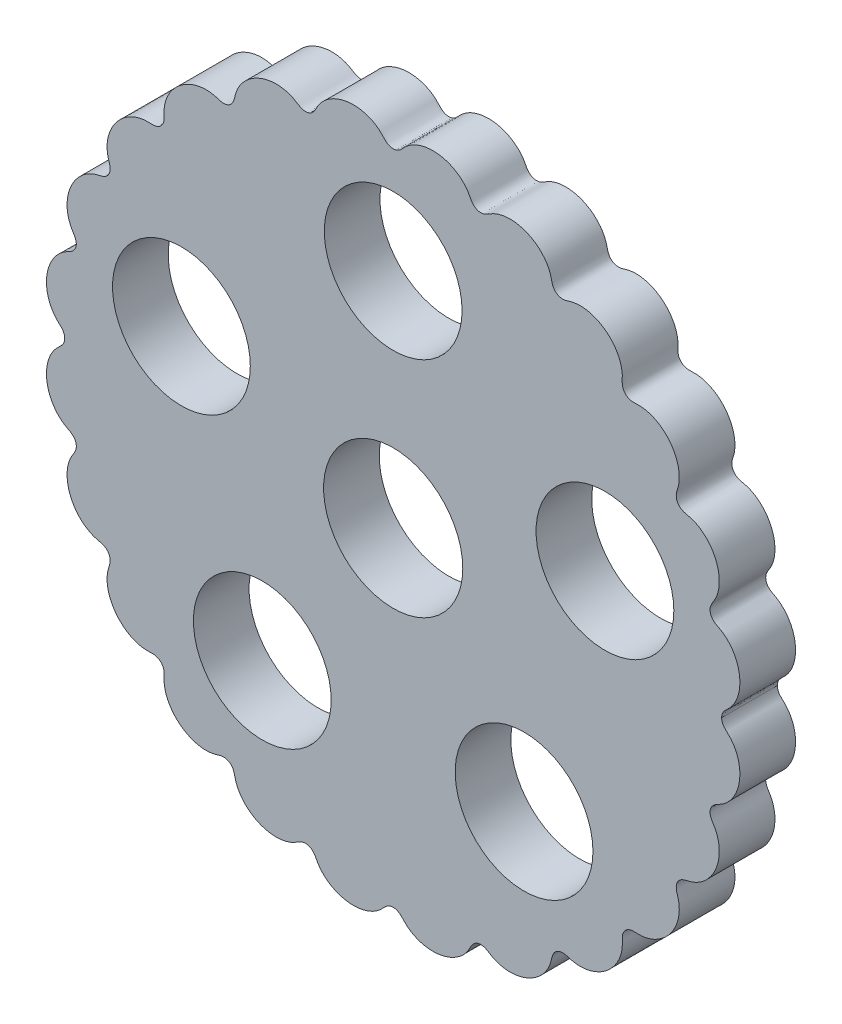
SolidWorks part; units mm, degrees
ref_plane "Plan de face" through (0, 0, 0) normal (0, 0, 1) x (1, 0, 0)
ref_plane "Plan de dessus" through (0, 0, 0) normal (0, 1, 0) x (1, 0, 0)
ref_plane "Plan de droite" through (0, 0, 0) normal (1, 0, 0) x (0, 0, -1)
sketch "Esquisse1" plane through (0, 0, 0) normal (0, 0, 1) x (1, 0, 0)
  line L0 (-1000, 0) -> (49000, 0) construction
  spline S0 degree 4 poles (22.9955, 6.6042) (22.9643, 6.5397) (22.914, 6.4032) (22.9023, 6.1862) (23.0214, 5.9244) (23.2219, 5.7605) (23.4288, 5.659) (23.6594, 5.5306) (23.9059, 5.3649) (24.1666, 5.1353) (24.4254, 4.835) (24.6422, 4.5029) (24.8162, 4.1468) (24.946, 3.7722) (25.0308, 3.385) (25.0698, 2.9906) (25.0624, 2.5943) (25.0079, 2.2017) (24.9068, 1.8224) (24.7781, 1.5066) (24.64, 1.2523) (24.5081, 1.0548) (24.3917, 0.9046) (24.2647, 0.7631) (24.1289, 0.6302) (24.012, 0.5251) (23.9248, 0.4355) (23.8688, 0.3622) (23.8363, 0.3122) (23.8082, 0.2597) (23.7852, 0.2044) (23.7697, 0.1547) (23.76, 0.1121) (23.7533, 0.0661) (23.7501, 0.0228) (23.7495, -0.004) (23.7513, -0.04) (23.7542, -0.0715) (23.7595, -0.1093) (23.7688, -0.1512) (23.7835, -0.1997) (23.8056, -0.2538) (23.8324, -0.3054) (23.8635, -0.3546) (23.9194, -0.4297) (24.009, -0.5227) (24.1313, -0.6322) (24.2737, -0.7721) (24.4392, -0.959) (24.6145, -1.2025) (24.7855, -1.5135) (24.9316, -1.8961) (25.0271, -2.299) (25.0708, -2.7153) (25.0622, -3.1311) (25.0033, -3.5401) (24.8958, -3.9363) (24.7419, -4.314) (24.5445, -4.6645) (24.307, -4.9822) (24.0331, -5.2614) (23.7654, -5.4667) (23.5164, -5.6129) (23.2956, -5.7243) (23.1195, -5.8363) (22.9763, -6.0087) (22.9044, -6.234) (22.925, -6.462) (23.0164, -6.6581) (23.1266, -6.8267) (23.2244, -6.9889) (23.3341, -7.1984) (23.4412, -7.4619) (23.5336, -7.7957) (23.5876, -8.2004) (23.5865, -8.623) (23.5267, -9.0558) (23.3808, -9.5868) (23.1436, -10.0885) (22.8209, -10.5434) (22.4327, -10.9196) (22.1006, -11.1627) (21.7948, -11.3267) (21.5321, -11.4304) (21.3065, -11.4954) (21.1232, -11.5381) (20.9306, -11.5808) (20.7385, -11.6689) (20.5325, -11.8672) (20.4495, -12.16) (20.5219, -12.4298) (20.6167, -12.7241) (20.6818, -13.0067) (20.7176, -13.3406) (20.7046, -13.7295) (20.6405, -14.1156) (20.5273, -14.4945) (20.3673, -14.8595) (20.1602, -15.2112) (19.9061, -15.5428) (19.6059, -15.8469) (19.261, -16.115) (18.8955, -16.3273) (18.5181, -16.4829) (18.1828, -16.5697) (17.9011, -16.6087) (17.6647, -16.6185) (17.4754, -16.6149) (17.2743, -16.6037) (17.0588, -16.6226) (16.851, -16.7187) (16.6918, -16.8937) (16.6141, -17.104) (16.6052, -17.3124) (16.6191, -17.5593) (16.617, -17.8481) (16.5731, -18.1826) (16.4683, -18.5594) (16.3118, -18.9239) (16.107, -19.2701) (15.8569, -19.5923) (15.5674, -19.8834) (15.2427, -20.1389) (14.8869, -20.3543) (14.5046, -20.5246) (14.1078, -20.6433) (13.7035, -20.7081) (13.2985, -20.7166) (12.9508, -20.673) (12.6603, -20.5981) (12.4161, -20.517) (12.2029, -20.4723) (11.9744, -20.5019) (11.768, -20.6211) (11.6281, -20.8042) (11.5602, -21.0112) (11.5084, -21.2632) (11.428, -21.5523) (11.2919, -21.8752) (11.082, -22.2216) (10.8237, -22.5394) (10.5226, -22.8236) (10.1839, -23.0696) (9.8195, -23.2701) (9.4358, -23.4235) (9.039, -23.5286) (8.6349, -23.5841) (8.2327, -23.5884) (7.8388, -23.5416) (7.4601, -23.444) (7.1484, -23.3148) (6.8973, -23.1723) (6.6904, -23.0367) (6.5054, -22.9402) (6.2844, -22.9024) (6.0534, -22.9528) (5.8662, -23.0846) (5.7421, -23.2618) (5.6512, -23.4416) (5.5596, -23.6073) (5.4331, -23.8072) (5.2584, -24.0316) (5.0155, -24.2786) (4.6921, -24.5276) (4.2308, -24.7924) (3.7121, -24.9769) (3.1672, -25.0695) (2.6142, -25.0665) (2.1723, -25.0046) (1.7597, -24.8871) (1.3831, -24.721) (1.0882, -24.5382) (0.867, -24.3625) (0.6979, -24.1997) (0.5693, -24.0623) (0.436, -23.9168) (0.2637, -23.7945) (-0.011, -23.7153) (-0.3061, -23.7898) (-0.5036, -23.9874) (-0.7111, -24.2166) (-0.9232, -24.4143) (-1.1945, -24.6122) (-1.5378, -24.7955) (-1.9042, -24.933) (-2.289, -25.0244) (-2.6851, -25.0684) (-3.0932, -25.0648) (-3.5074, -25.0106) (-3.9209, -24.9026) (-4.3256, -24.738) (-4.6921, -24.5276) (-5.0155, -24.2786) (-5.2584, -24.0316) (-5.4331, -23.8072) (-5.5596, -23.6073) (-5.6512, -23.4416) (-5.7421, -23.2618) (-5.8662, -23.0846) (-6.0534, -22.9528) (-6.2844, -22.9024) (-6.5054, -22.9402) (-6.6904, -23.0367) (-6.8973, -23.1723) (-7.1484, -23.3148) (-7.4601, -23.444) (-7.8388, -23.5416) (-8.2327, -23.5884) (-8.6349, -23.5841) (-9.039, -23.5286) (-9.4358, -23.4235) (-9.8195, -23.2701) (-10.1839, -23.0696) (-10.5226, -22.8236) (-10.8237, -22.5394) (-11.082, -22.2216) (-11.2919, -21.8752) (-11.428, -21.5523) (-11.5084, -21.2632) (-11.5602, -21.0112) (-11.6281, -20.8042) (-11.768, -20.6211) (-11.9744, -20.5019) (-12.2029, -20.4723) (-12.4161, -20.517) (-12.6603, -20.5981) (-12.9508, -20.673) (-13.2985, -20.7166) (-13.7035, -20.7081) (-14.1078, -20.6433) (-14.6048, -20.4946) (-15.1642, -20.2163) (-15.6552, -19.8308) (-16.055, -19.3579) (-16.3118, -18.9239) (-16.4683, -18.5594) (-16.5731, -18.1826) (-16.617, -17.8481) (-16.6191, -17.5593) (-16.6052, -17.3124) (-16.6141, -17.104) (-16.6918, -16.8937) (-16.851, -16.7187) (-17.0588, -16.6226) (-17.2743, -16.6037) (-17.4754, -16.6149) (-17.6647, -16.6185) (-17.9011, -16.6087) (-18.1828, -16.5697) (-18.5181, -16.4829) (-18.8955, -16.3273) (-19.261, -16.1151) (-19.6059, -15.8469) (-19.9061, -15.5428) (-20.1602, -15.2112) (-20.3673, -14.8595) (-20.5273, -14.4945) (-20.6405, -14.1156) (-20.7046, -13.7294) (-20.7175, -13.3407) (-20.6818, -13.0066) (-20.6166, -12.7243) (-20.522, -12.4295) (-20.4494, -12.1605) (-20.5243, -11.8962) (-20.683, -11.7227) (-20.8176, -11.632) (-20.958, -11.5755) (-21.1234, -11.5373) (-21.3064, -11.4958) (-21.5321, -11.4302) (-21.7948, -11.3268) (-22.1006, -11.1626) (-22.4327, -10.9196) (-22.7408, -10.6211) (-23.0153, -10.2693) (-23.2393, -9.8862) (-23.4104, -9.4792) (-23.5267, -9.0558) (-23.5865, -8.623) (-23.5876, -8.2004) (-23.5336, -7.7957) (-23.4412, -7.4619) (-23.3341, -7.1984) (-23.2244, -6.9889) (-23.1266, -6.8267) (-23.0164, -6.6581) (-22.925, -6.462) (-22.9044, -6.234) (-22.9763, -6.0087) (-23.1195, -5.8363) (-23.2956, -5.7243) (-23.5164, -5.6129) (-23.7654, -5.4667) (-24.0331, -5.2614) (-24.307, -4.9822) (-24.5445, -4.6645) (-24.7419, -4.314) (-24.8958, -3.9363) (-25.0033, -3.5401) (-25.0622, -3.1311) (-25.0708, -2.7153) (-25.0271, -2.299) (-24.9316, -1.8961) (-24.7855, -1.5135) (-24.6145, -1.2025) (-24.4393, -0.959) (-24.2737, -0.7721) (-24.1313, -0.6321) (-23.9982, -0.5131) (-23.8995, -0.4084) (-23.8391, -0.3182) (-23.8055, -0.2539) (-23.7835, -0.1997) (-23.7688, -0.1512) (-23.7595, -0.1093) (-23.7542, -0.0715) (-23.7513, -0.04) (-23.7495, -0.0037) (-23.7502, 0.0234) (-23.7534, 0.0677) (-23.7604, 0.1144) (-23.7705, 0.1578) (-23.7867, 0.2087) (-23.8107, 0.2649) (-23.8399, 0.3183) (-23.8736, 0.369) (-23.9317, 0.4432) (-24.0215, 0.5339) (-24.141, 0.6413) (-24.279, 0.7779) (-24.4075, 0.9235) (-24.5249, 1.0783) (-24.6575, 1.2816) (-24.7976, 1.5478) (-24.9275, 1.8824) (-25.0256, 2.2876) (-25.071, 2.7111) (-25.0623, 3.1368) (-25.0002, 3.5582) (-24.8859, 3.9683) (-24.7199, 4.3608) (-24.4999, 4.7349) (-24.2231, 5.0813) (-23.9331, 5.3469) (-23.6469, 5.5411) (-23.3456, 5.7009) (-23.0735, 5.8417) (-22.8982, 6.1368) (-22.9147, 6.4027) (-22.9638, 6.54) (-22.9956, 6.6042) knots 0 0 0 0 0 0.002762 0.005524 0.008057 0.010589 0.012487 0.014385 0.018181 0.021977 0.025773 0.029569 0.033366 0.037162 0.040959 0.044755 0.048552 0.052348 0.056144 0.059791 0.061614 0.063437 0.06526 0.067083 0.068906 0.070729 0.071301 0.071873 0.072445 0.073016 0.073588 0.07416 0.074446 0.074731 0.075303 0.075582 0.075861 0.07614 0.076419 0.076977 0.077535 0.078093 0.078652 0.07921 0.079768 0.081683 0.083599 0.085515 0.08743 0.091261 0.095093 0.099101 0.103109 0.107118 0.111126 0.115032 0.118938 0.122843 0.126749 0.130438 0.134127 0.137815 0.13966 0.141504 0.143638 0.145771 0.148068 0.150364 0.15218 0.153996 0.155812 0.157628 0.16126 0.164892 0.169075 0.173257 0.177439 0.181621 0.190162 0.194433 0.198704 0.20231 0.205917 0.20772 0.209523 0.211327 0.21313 0.215313 0.217496 0.222107 0.223949 0.225791 0.229476 0.23316 0.236844 0.240662 0.24448 0.248298 0.252116 0.256299 0.260481 0.264663 0.268845 0.272477 0.276109 0.277925 0.279741 0.281557 0.283373 0.28567 0.287966 0.2901 0.292233 0.294078 0.295922 0.299611 0.3033 0.306988 0.310894 0.3148 0.318706 0.322612 0.32662 0.330628 0.334637 0.338645 0.342476 0.346307 0.350139 0.352054 0.35397 0.356202 0.358434 0.360667 0.362899 0.364815 0.36673 0.370561 0.374393 0.378224 0.382232 0.386241 0.390249 0.394257 0.398163 0.402069 0.405975 0.40988 0.413569 0.417258 0.420947 0.422791 0.424635 0.426769 0.428902 0.431199 0.433495 0.435311 0.437127 0.438943 0.440759 0.444392 0.448024 0.452206 0.456388 0.464752 0.469023 0.473294 0.477564 0.481835 0.485441 0.489048 0.490851 0.492655 0.494458 0.496261 0.498444 0.500627 0.505239 0.507081 0.508923 0.512607 0.516291 0.519975 0.523793 0.527611 0.53143 0.535248 0.53943 0.543612 0.547794 0.551976 0.555609 0.559241 0.561057 0.562873 0.564689 0.566505 0.568801 0.571098 0.573231 0.575365 0.577209 0.579053 0.582742 0.586431 0.59012 0.594025 0.597931 0.601837 0.605743 0.609751 0.61376 0.617768 0.621776 0.625607 0.629439 0.63327 0.635186 0.637101 0.639333 0.641566 0.643798 0.64603 0.647946 0.649861 0.653693 0.657524 0.661355 0.665364 0.669372 0.677388 0.6852 0.689106 0.693012 0.6967 0.700389 0.704078 0.705922 0.707767 0.7099 0.712034 0.71433 0.716627 0.718443 0.720259 0.722075 0.723891 0.727523 0.731155 0.735337 0.739519 0.743701 0.747884 0.751702 0.75552 0.759338 0.763156 0.76684 0.770525 0.774209 0.776051 0.777893 0.782504 0.784687 0.785779 0.78687 0.788673 0.790477 0.79228 0.794083 0.79769 0.801296 0.805567 0.809838 0.814108 0.818379 0.822561 0.826743 0.830926 0.835108 0.83874 0.842372 0.844188 0.846004 0.84782 0.849636 0.851932 0.854229 0.856362 0.858496 0.86034 0.862185 0.865873 0.869562 0.873251 0.877157 0.881063 0.884968 0.888874 0.892882 0.896891 0.900899 0.904907 0.908739 0.91257 0.914486 0.916401 0.918317 0.920232 0.921349 0.921907 0.922465 0.923023 0.923581 0.92386 0.924139 0.924418 0.924697 0.925281 0.925573 0.925865 0.926449 0.927033 0.927617 0.928201 0.928785 0.929369 0.931232 0.933095 0.934957 0.93682 0.938683 0.940546 0.944272 0.94835 0.952428 0.956506 0.960584 0.964661 0.968739 0.972817 0.976894 0.98129 0.985685 0.987883 0.99008 0.994476 0.997238 1 1 1 1 1 construction
  spline S1 degree 4 poles (23.75, 0) (23.75, -0.0062) (23.7502, -0.0186) (23.7513, -0.04) (23.7542, -0.0715) (23.7595, -0.1093) (23.7688, -0.1512) (23.7835, -0.1997) (23.8056, -0.2538) (23.8324, -0.3054) (23.8635, -0.3546) (23.9194, -0.4297) (24.009, -0.5227) (24.1313, -0.6322) (24.2737, -0.7721) (24.4392, -0.959) (24.6145, -1.2025) (24.7855, -1.5135) (24.9316, -1.8961) (25.0271, -2.299) (25.0708, -2.7153) (25.0622, -3.1311) (25.0033, -3.5401) (24.8958, -3.9363) (24.7419, -4.314) (24.5445, -4.6645) (24.307, -4.9822) (24.0331, -5.2614) (23.7654, -5.4667) (23.5164, -5.6129) (23.2956, -5.7243) (23.1195, -5.8363) (22.9763, -6.0087) (22.9044, -6.234) (22.925, -6.462) (23.0164, -6.6581) (23.1266, -6.8267) (23.2244, -6.9889) (23.3341, -7.1984) (23.4412, -7.4619) (23.5336, -7.7957) (23.5876, -8.2004) (23.5865, -8.623) (23.5267, -9.0558) (23.3808, -9.5868) (23.1436, -10.0885) (22.8209, -10.5434) (22.4327, -10.9196) (22.1006, -11.1627) (21.7948, -11.3267) (21.5321, -11.4304) (21.3065, -11.4954) (21.1232, -11.5381) (20.9306, -11.5808) (20.7385, -11.6689) (20.5325, -11.8672) (20.4495, -12.16) (20.5219, -12.4298) (20.6167, -12.7241) (20.6818, -13.0067) (20.7176, -13.3406) (20.7046, -13.7295) (20.6405, -14.1156) (20.5273, -14.4945) (20.3673, -14.8595) (20.1602, -15.2112) (19.9061, -15.5428) (19.6059, -15.8469) (19.261, -16.115) (18.8955, -16.3273) (18.5181, -16.4829) (18.1828, -16.5697) (17.9011, -16.6087) (17.6647, -16.6185) (17.4754, -16.6149) (17.2743, -16.6037) (17.0588, -16.6226) (16.851, -16.7187) (16.6918, -16.8937) (16.6141, -17.104) (16.6052, -17.3124) (16.6191, -17.5593) (16.617, -17.8481) (16.5731, -18.1826) (16.4683, -18.5594) (16.3118, -18.9239) (16.107, -19.2701) (15.8569, -19.5923) (15.5674, -19.8834) (15.2427, -20.1389) (14.8869, -20.3543) (14.5046, -20.5246) (14.1078, -20.6433) (13.7035, -20.7081) (13.2985, -20.7166) (12.9508, -20.673) (12.6603, -20.5981) (12.4161, -20.517) (12.2029, -20.4723) (11.9744, -20.5019) (11.768, -20.6211) (11.6281, -20.8042) (11.5602, -21.0112) (11.5084, -21.2632) (11.428, -21.5523) (11.2919, -21.8752) (11.082, -22.2216) (10.8237, -22.5394) (10.5226, -22.8236) (10.1839, -23.0696) (9.8195, -23.2701) (9.4358, -23.4235) (9.039, -23.5286) (8.6349, -23.5841) (8.2327, -23.5884) (7.8388, -23.5416) (7.4601, -23.444) (7.1484, -23.3148) (6.8973, -23.1723) (6.6904, -23.0367) (6.5054, -22.9402) (6.2844, -22.9024) (6.0534, -22.9528) (5.8662, -23.0846) (5.7421, -23.2618) (5.6512, -23.4416) (5.5596, -23.6073) (5.4331, -23.8072) (5.2584, -24.0316) (5.0155, -24.2786) (4.6921, -24.5276) (4.2308, -24.7924) (3.7121, -24.9769) (3.1672, -25.0695) (2.6142, -25.0665) (2.1723, -25.0046) (1.7597, -24.8871) (1.3831, -24.721) (1.0882, -24.5382) (0.867, -24.3625) (0.6979, -24.1997) (0.5693, -24.0623) (0.436, -23.9168) (0.2637, -23.7945) (-0.011, -23.7153) (-0.3061, -23.7898) (-0.5036, -23.9874) (-0.7111, -24.2166) (-0.9232, -24.4143) (-1.1945, -24.6122) (-1.5378, -24.7955) (-1.9042, -24.933) (-2.289, -25.0244) (-2.6851, -25.0684) (-3.0932, -25.0648) (-3.5074, -25.0106) (-3.9209, -24.9026) (-4.3256, -24.738) (-4.6921, -24.5276) (-5.0155, -24.2786) (-5.2584, -24.0316) (-5.4331, -23.8072) (-5.5596, -23.6073) (-5.6512, -23.4416) (-5.7421, -23.2618) (-5.8662, -23.0846) (-6.0534, -22.9528) (-6.2844, -22.9024) (-6.5054, -22.9402) (-6.6904, -23.0367) (-6.8973, -23.1723) (-7.1484, -23.3148) (-7.4601, -23.444) (-7.8388, -23.5416) (-8.2327, -23.5884) (-8.6349, -23.5841) (-9.039, -23.5286) (-9.4358, -23.4235) (-9.8195, -23.2701) (-10.1839, -23.0696) (-10.5226, -22.8236) (-10.8237, -22.5394) (-11.082, -22.2216) (-11.2919, -21.8752) (-11.428, -21.5523) (-11.5084, -21.2632) (-11.5602, -21.0112) (-11.6281, -20.8042) (-11.768, -20.6211) (-11.9744, -20.5019) (-12.2029, -20.4723) (-12.4161, -20.517) (-12.6603, -20.5981) (-12.9508, -20.673) (-13.2985, -20.7166) (-13.7035, -20.7081) (-14.1078, -20.6433) (-14.6048, -20.4946) (-15.1642, -20.2163) (-15.6552, -19.8308) (-16.055, -19.3579) (-16.3118, -18.9239) (-16.4683, -18.5594) (-16.5731, -18.1826) (-16.617, -17.8481) (-16.6191, -17.5593) (-16.6052, -17.3124) (-16.6141, -17.104) (-16.6918, -16.8937) (-16.851, -16.7187) (-17.0588, -16.6226) (-17.2743, -16.6037) (-17.4754, -16.6149) (-17.6647, -16.6185) (-17.9011, -16.6087) (-18.1828, -16.5697) (-18.5181, -16.4829) (-18.8955, -16.3273) (-19.261, -16.1151) (-19.6059, -15.8469) (-19.9061, -15.5428) (-20.1602, -15.2112) (-20.3673, -14.8595) (-20.5273, -14.4945) (-20.6405, -14.1156) (-20.7046, -13.7294) (-20.7175, -13.3407) (-20.6818, -13.0066) (-20.6166, -12.7243) (-20.522, -12.4295) (-20.4494, -12.1605) (-20.5243, -11.8962) (-20.683, -11.7227) (-20.8176, -11.632) (-20.958, -11.5755) (-21.1234, -11.5373) (-21.3064, -11.4958) (-21.5321, -11.4302) (-21.7948, -11.3268) (-22.1006, -11.1626) (-22.4327, -10.9196) (-22.7408, -10.6211) (-23.0153, -10.2693) (-23.2393, -9.8862) (-23.4104, -9.4792) (-23.5267, -9.0558) (-23.5865, -8.623) (-23.5876, -8.2004) (-23.5336, -7.7957) (-23.4412, -7.4619) (-23.3341, -7.1984) (-23.2244, -6.9889) (-23.1266, -6.8267) (-23.0164, -6.6581) (-22.925, -6.462) (-22.9044, -6.234) (-22.9763, -6.0087) (-23.1195, -5.8363) (-23.2956, -5.7243) (-23.5164, -5.6129) (-23.7654, -5.4667) (-24.0331, -5.2614) (-24.307, -4.9822) (-24.5445, -4.6645) (-24.7419, -4.314) (-24.8958, -3.9363) (-25.0033, -3.5401) (-25.0622, -3.1311) (-25.0708, -2.7153) (-25.0271, -2.299) (-24.9316, -1.8961) (-24.7855, -1.5135) (-24.6145, -1.2025) (-24.4393, -0.959) (-24.2737, -0.7721) (-24.1313, -0.6321) (-23.9982, -0.5131) (-23.8995, -0.4084) (-23.8391, -0.3182) (-23.8055, -0.2539) (-23.7835, -0.1997) (-23.7688, -0.1512) (-23.7595, -0.1093) (-23.7542, -0.0715) (-23.7513, -0.04) (-23.7502, -0.0186) (-23.75, -0.0062) (-23.75, 0) knots 0.075303 0.075303 0.075303 0.075303 0.075303 0.075582 0.075861 0.07614 0.076419 0.076977 0.077535 0.078093 0.078652 0.07921 0.079768 0.081683 0.083599 0.085515 0.08743 0.091261 0.095093 0.099101 0.103109 0.107118 0.111126 0.115032 0.118938 0.122843 0.126749 0.130438 0.134127 0.137815 0.13966 0.141504 0.143638 0.145771 0.148068 0.150364 0.15218 0.153996 0.155812 0.157628 0.16126 0.164892 0.169075 0.173257 0.177439 0.181621 0.190162 0.194433 0.198704 0.20231 0.205917 0.20772 0.209523 0.211327 0.21313 0.215313 0.217496 0.222107 0.223949 0.225791 0.229476 0.23316 0.236844 0.240662 0.24448 0.248298 0.252116 0.256299 0.260481 0.264663 0.268845 0.272477 0.276109 0.277925 0.279741 0.281557 0.283373 0.28567 0.287966 0.2901 0.292233 0.294078 0.295922 0.299611 0.3033 0.306988 0.310894 0.3148 0.318706 0.322612 0.32662 0.330628 0.334637 0.338645 0.342476 0.346307 0.350139 0.352054 0.35397 0.356202 0.358434 0.360667 0.362899 0.364815 0.36673 0.370561 0.374393 0.378224 0.382232 0.386241 0.390249 0.394257 0.398163 0.402069 0.405975 0.40988 0.413569 0.417258 0.420947 0.422791 0.424635 0.426769 0.428902 0.431199 0.433495 0.435311 0.437127 0.438943 0.440759 0.444392 0.448024 0.452206 0.456388 0.464752 0.469023 0.473294 0.477564 0.481835 0.485441 0.489048 0.490851 0.492655 0.494458 0.496261 0.498444 0.500627 0.505239 0.507081 0.508923 0.512607 0.516291 0.519975 0.523793 0.527611 0.53143 0.535248 0.53943 0.543612 0.547794 0.551976 0.555609 0.559241 0.561057 0.562873 0.564689 0.566505 0.568801 0.571098 0.573231 0.575365 0.577209 0.579053 0.582742 0.586431 0.59012 0.594025 0.597931 0.601837 0.605743 0.609751 0.61376 0.617768 0.621776 0.625607 0.629439 0.63327 0.635186 0.637101 0.639333 0.641566 0.643798 0.64603 0.647946 0.649861 0.653693 0.657524 0.661355 0.665364 0.669372 0.677388 0.6852 0.689106 0.693012 0.6967 0.700389 0.704078 0.705922 0.707767 0.7099 0.712034 0.71433 0.716627 0.718443 0.720259 0.722075 0.723891 0.727523 0.731155 0.735337 0.739519 0.743701 0.747884 0.751702 0.75552 0.759338 0.763156 0.76684 0.770525 0.774209 0.776051 0.777893 0.782504 0.784687 0.785779 0.78687 0.788673 0.790477 0.79228 0.794083 0.79769 0.801296 0.805567 0.809838 0.814108 0.818379 0.822561 0.826743 0.830926 0.835108 0.83874 0.842372 0.844188 0.846004 0.84782 0.849636 0.851932 0.854229 0.856362 0.858496 0.86034 0.862185 0.865873 0.869562 0.873251 0.877157 0.881063 0.884968 0.888874 0.892882 0.896891 0.900899 0.904907 0.908739 0.91257 0.914486 0.916401 0.918317 0.920232 0.921349 0.921907 0.922465 0.923023 0.923581 0.92386 0.924139 0.924418 0.924697 0.924697 0.924697 0.924697 0.924697 construction
  spline S2 degree 4 poles (23.75, 0) (23.75, 0.0062) (23.7502, 0.0186) (23.7513, 0.04) (23.7542, 0.0715) (23.7595, 0.1093) (23.7688, 0.1512) (23.7835, 0.1997) (23.8056, 0.2538) (23.8324, 0.3054) (23.8635, 0.3546) (23.9194, 0.4297) (24.009, 0.5227) (24.1313, 0.6322) (24.2737, 0.7721) (24.4392, 0.959) (24.6145, 1.2025) (24.7855, 1.5135) (24.9316, 1.8961) (25.0271, 2.299) (25.0708, 2.7153) (25.0622, 3.1311) (25.0033, 3.5401) (24.8958, 3.9363) (24.7419, 4.314) (24.5445, 4.6645) (24.307, 4.9822) (24.0331, 5.2614) (23.7654, 5.4667) (23.5164, 5.6129) (23.2956, 5.7243) (23.1195, 5.8363) (22.9763, 6.0087) (22.9044, 6.234) (22.925, 6.462) (23.0164, 6.6581) (23.1266, 6.8267) (23.2244, 6.9889) (23.3341, 7.1984) (23.4412, 7.4619) (23.5336, 7.7957) (23.5876, 8.2004) (23.5865, 8.623) (23.5267, 9.0558) (23.3808, 9.5868) (23.1436, 10.0885) (22.8209, 10.5434) (22.4327, 10.9196) (22.1006, 11.1627) (21.7948, 11.3267) (21.5321, 11.4304) (21.3065, 11.4954) (21.1232, 11.5381) (20.9306, 11.5808) (20.7385, 11.6689) (20.5325, 11.8672) (20.4495, 12.16) (20.5219, 12.4298) (20.6167, 12.7241) (20.6818, 13.0067) (20.7176, 13.3406) (20.7046, 13.7295) (20.6405, 14.1156) (20.5273, 14.4945) (20.3673, 14.8595) (20.1602, 15.2112) (19.9061, 15.5428) (19.6059, 15.8469) (19.261, 16.115) (18.8955, 16.3273) (18.5181, 16.4829) (18.1828, 16.5697) (17.9011, 16.6087) (17.6647, 16.6185) (17.4754, 16.6149) (17.2743, 16.6037) (17.0588, 16.6226) (16.851, 16.7187) (16.6918, 16.8937) (16.6141, 17.104) (16.6052, 17.3124) (16.6191, 17.5593) (16.617, 17.8481) (16.5731, 18.1826) (16.4683, 18.5594) (16.3118, 18.9239) (16.107, 19.2701) (15.8569, 19.5923) (15.5674, 19.8834) (15.2427, 20.1389) (14.8869, 20.3543) (14.5046, 20.5246) (14.1078, 20.6433) (13.7035, 20.7081) (13.2985, 20.7166) (12.9508, 20.673) (12.6603, 20.5981) (12.4161, 20.517) (12.2029, 20.4723) (11.9744, 20.5019) (11.768, 20.6211) (11.6281, 20.8042) (11.5602, 21.0112) (11.5084, 21.2632) (11.428, 21.5523) (11.2919, 21.8752) (11.082, 22.2216) (10.8237, 22.5394) (10.5226, 22.8236) (10.1839, 23.0696) (9.8195, 23.2701) (9.4358, 23.4235) (9.039, 23.5286) (8.6349, 23.5841) (8.2327, 23.5884) (7.8388, 23.5416) (7.4601, 23.444) (7.1484, 23.3148) (6.8973, 23.1723) (6.6904, 23.0367) (6.5054, 22.9402) (6.2844, 22.9024) (6.0534, 22.9528) (5.8662, 23.0846) (5.7421, 23.2618) (5.6512, 23.4416) (5.5596, 23.6073) (5.4331, 23.8072) (5.2584, 24.0316) (5.0155, 24.2786) (4.6921, 24.5276) (4.2308, 24.7924) (3.7121, 24.9769) (3.1672, 25.0695) (2.6142, 25.0665) (2.1723, 25.0046) (1.7597, 24.8871) (1.3831, 24.721) (1.0882, 24.5382) (0.867, 24.3625) (0.6979, 24.1997) (0.5693, 24.0623) (0.436, 23.9168) (0.2637, 23.7945) (-0.011, 23.7153) (-0.3061, 23.7898) (-0.5036, 23.9874) (-0.7111, 24.2166) (-0.9232, 24.4143) (-1.1945, 24.6122) (-1.5378, 24.7955) (-1.9042, 24.933) (-2.289, 25.0244) (-2.6851, 25.0684) (-3.0932, 25.0648) (-3.5074, 25.0106) (-3.9209, 24.9026) (-4.3256, 24.738) (-4.6921, 24.5276) (-5.0155, 24.2786) (-5.2584, 24.0316) (-5.4331, 23.8072) (-5.5596, 23.6073) (-5.6512, 23.4416) (-5.7421, 23.2618) (-5.8662, 23.0846) (-6.0534, 22.9528) (-6.2844, 22.9024) (-6.5054, 22.9402) (-6.6904, 23.0367) (-6.8973, 23.1723) (-7.1484, 23.3148) (-7.4601, 23.444) (-7.8388, 23.5416) (-8.2327, 23.5884) (-8.6349, 23.5841) (-9.039, 23.5286) (-9.4358, 23.4235) (-9.8195, 23.2701) (-10.1839, 23.0696) (-10.5226, 22.8236) (-10.8237, 22.5394) (-11.082, 22.2216) (-11.2919, 21.8752) (-11.428, 21.5523) (-11.5084, 21.2632) (-11.5602, 21.0112) (-11.6281, 20.8042) (-11.768, 20.6211) (-11.9744, 20.5019) (-12.2029, 20.4723) (-12.4161, 20.517) (-12.6603, 20.5981) (-12.9508, 20.673) (-13.2985, 20.7166) (-13.7035, 20.7081) (-14.1078, 20.6433) (-14.6048, 20.4946) (-15.1642, 20.2163) (-15.6552, 19.8308) (-16.055, 19.3579) (-16.3118, 18.9239) (-16.4683, 18.5594) (-16.5731, 18.1826) (-16.617, 17.8481) (-16.6191, 17.5593) (-16.6052, 17.3124) (-16.6141, 17.104) (-16.6918, 16.8937) (-16.851, 16.7187) (-17.0588, 16.6226) (-17.2743, 16.6037) (-17.4754, 16.6149) (-17.6647, 16.6185) (-17.9011, 16.6087) (-18.1828, 16.5697) (-18.5181, 16.4829) (-18.8955, 16.3273) (-19.261, 16.1151) (-19.6059, 15.8469) (-19.9061, 15.5428) (-20.1602, 15.2112) (-20.3673, 14.8595) (-20.5273, 14.4945) (-20.6405, 14.1156) (-20.7046, 13.7294) (-20.7175, 13.3407) (-20.6818, 13.0066) (-20.6166, 12.7243) (-20.522, 12.4295) (-20.4494, 12.1605) (-20.5243, 11.8962) (-20.683, 11.7227) (-20.8176, 11.632) (-20.958, 11.5755) (-21.1234, 11.5373) (-21.3064, 11.4958) (-21.5321, 11.4302) (-21.7948, 11.3268) (-22.1006, 11.1626) (-22.4327, 10.9196) (-22.7408, 10.6211) (-23.0153, 10.2693) (-23.2393, 9.8862) (-23.4104, 9.4792) (-23.5267, 9.0558) (-23.5865, 8.623) (-23.5876, 8.2004) (-23.5336, 7.7957) (-23.4412, 7.4619) (-23.3341, 7.1984) (-23.2244, 6.9889) (-23.1266, 6.8267) (-23.0164, 6.6581) (-22.925, 6.462) (-22.9044, 6.234) (-22.9763, 6.0087) (-23.1195, 5.8363) (-23.2956, 5.7243) (-23.5164, 5.6129) (-23.7654, 5.4667) (-24.0331, 5.2614) (-24.307, 4.9822) (-24.5445, 4.6645) (-24.7419, 4.314) (-24.8958, 3.9363) (-25.0033, 3.5401) (-25.0622, 3.1311) (-25.0708, 2.7153) (-25.0271, 2.299) (-24.9316, 1.8961) (-24.7855, 1.5135) (-24.6145, 1.2025) (-24.4393, 0.959) (-24.2737, 0.7721) (-24.1313, 0.6321) (-23.9982, 0.5131) (-23.8995, 0.4084) (-23.8391, 0.3182) (-23.8055, 0.2539) (-23.7835, 0.1997) (-23.7688, 0.1512) (-23.7595, 0.1093) (-23.7542, 0.0715) (-23.7513, 0.04) (-23.7502, 0.0186) (-23.75, 0.0062) (-23.75, 0) knots 0.075303 0.075303 0.075303 0.075303 0.075303 0.075582 0.075861 0.07614 0.076419 0.076977 0.077535 0.078093 0.078652 0.07921 0.079768 0.081683 0.083599 0.085515 0.08743 0.091261 0.095093 0.099101 0.103109 0.107118 0.111126 0.115032 0.118938 0.122843 0.126749 0.130438 0.134127 0.137815 0.13966 0.141504 0.143638 0.145771 0.148068 0.150364 0.15218 0.153996 0.155812 0.157628 0.16126 0.164892 0.169075 0.173257 0.177439 0.181621 0.190162 0.194433 0.198704 0.20231 0.205917 0.20772 0.209523 0.211327 0.21313 0.215313 0.217496 0.222107 0.223949 0.225791 0.229476 0.23316 0.236844 0.240662 0.24448 0.248298 0.252116 0.256299 0.260481 0.264663 0.268845 0.272477 0.276109 0.277925 0.279741 0.281557 0.283373 0.28567 0.287966 0.2901 0.292233 0.294078 0.295922 0.299611 0.3033 0.306988 0.310894 0.3148 0.318706 0.322612 0.32662 0.330628 0.334637 0.338645 0.342476 0.346307 0.350139 0.352054 0.35397 0.356202 0.358434 0.360667 0.362899 0.364815 0.36673 0.370561 0.374393 0.378224 0.382232 0.386241 0.390249 0.394257 0.398163 0.402069 0.405975 0.40988 0.413569 0.417258 0.420947 0.422791 0.424635 0.426769 0.428902 0.431199 0.433495 0.435311 0.437127 0.438943 0.440759 0.444392 0.448024 0.452206 0.456388 0.464752 0.469023 0.473294 0.477564 0.481835 0.485441 0.489048 0.490851 0.492655 0.494458 0.496261 0.498444 0.500627 0.505239 0.507081 0.508923 0.512607 0.516291 0.519975 0.523793 0.527611 0.53143 0.535248 0.53943 0.543612 0.547794 0.551976 0.555609 0.559241 0.561057 0.562873 0.564689 0.566505 0.568801 0.571098 0.573231 0.575365 0.577209 0.579053 0.582742 0.586431 0.59012 0.594025 0.597931 0.601837 0.605743 0.609751 0.61376 0.617768 0.621776 0.625607 0.629439 0.63327 0.635186 0.637101 0.639333 0.641566 0.643798 0.64603 0.647946 0.649861 0.653693 0.657524 0.661355 0.665364 0.669372 0.677388 0.6852 0.689106 0.693012 0.6967 0.700389 0.704078 0.705922 0.707767 0.7099 0.712034 0.71433 0.716627 0.718443 0.720259 0.722075 0.723891 0.727523 0.731155 0.735337 0.739519 0.743701 0.747884 0.751702 0.75552 0.759338 0.763156 0.76684 0.770525 0.774209 0.776051 0.777893 0.782504 0.784687 0.785779 0.78687 0.788673 0.790477 0.79228 0.794083 0.79769 0.801296 0.805567 0.809838 0.814108 0.818379 0.822561 0.826743 0.830926 0.835108 0.83874 0.842372 0.844188 0.846004 0.84782 0.849636 0.851932 0.854229 0.856362 0.858496 0.86034 0.862185 0.865873 0.869562 0.873251 0.877157 0.881063 0.884968 0.888874 0.892882 0.896891 0.900899 0.904907 0.908739 0.91257 0.914486 0.916401 0.918317 0.920232 0.921349 0.921907 0.922465 0.923023 0.923581 0.92386 0.924139 0.924418 0.924697 0.924697 0.924697 0.924697 0.924697 construction
  spline S3 degree 1 poles (23.6, 0) (-23.6, 0) knots 0 0 1 1 construction
  spline S4 degree 1 poles (23.6, 0) (-23.6, 0) knots 0 0 1 1 construction
  spline S5 degree 3 poles (23.6, 0) (23.6, 0.1413) (23.695, 0.4365) (23.9841, 0.7) (24.2141, 0.9221) (24.4859, 1.2659) (24.7382, 1.7532) (24.9028, 2.3953) (24.9291, 3.0585) (24.8201, 3.7136) (24.5796, 4.3319) (24.2145, 4.8837) (23.8098, 5.2567) (23.4446, 5.4862) (23.1218, 5.6322) (22.8058, 5.9504) (22.7343, 6.405) (22.9149, 6.792) (23.1004, 7.0616) (23.2413, 7.3578) (23.3797, 7.7712) (23.4552, 8.3172) (23.4005, 8.9778) (23.2102, 9.614) (22.8949, 10.1984) (22.4664, 10.7042) (22.027, 11.0368) (21.6368, 11.2314) (21.3278, 11.341) (21.0066, 11.4006) (20.6047, 11.5464) (20.3336, 11.9192) (20.3321, 12.366) (20.4572, 12.6992) (20.5531, 13.1186) (20.5755, 13.6691) (20.4435, 14.3172) (20.1764, 14.9246) (19.7902, 15.4648) (19.3027, 15.9152) (18.7322, 16.2529) (18.2093, 16.419) (17.7739, 16.4699) (17.4549, 16.4641) (17.0624, 16.4473) (16.6542, 16.6542) (16.4474, 17.0623) (16.464, 17.4549) (16.47, 17.7738) (16.419, 18.2094) (16.2529, 18.7322) (15.9152, 19.3027) (15.4649, 19.7902) (14.9246, 20.1764) (14.3173, 20.4435) (13.669, 20.5755) (13.119, 20.5531) (12.6986, 20.4572) (12.367, 20.3322) (11.9185, 20.3338) (11.5466, 20.6046) (11.4006, 21.0058) (11.3413, 21.3277) (11.2312, 21.6369) (11.0369, 22.0269) (10.7042, 22.4665) (10.1983, 22.8949) (9.614, 23.2102) (8.9778, 23.4005) (8.3172, 23.4552) (7.7711, 23.3797) (7.3579, 23.2413) (7.0615, 23.1004) (6.7919, 22.9149) (6.4049, 22.7343) (5.9505, 22.8058) (5.6322, 23.1217) (5.4863, 23.4443) (5.2567, 23.81) (4.8837, 24.2144) (4.3318, 24.5796) (3.7136, 24.8201) (3.0585, 24.9291) (2.3953, 24.9028) (1.7531, 24.7382) (1.2659, 24.4859) (0.9221, 24.2142) (0.7002, 23.9842) (0.4345, 23.6948) (0.0001, 23.5526) (-0.4343, 23.6948) (-0.7014, 23.9846) (-0.9213, 24.2137) (-1.2665, 24.4862) (-1.753, 24.7381) (-2.3954, 24.9028) (-3.0585, 24.9291) (-3.7136, 24.8201) (-4.3319, 24.5796) (-4.8837, 24.2144) (-5.2567, 23.81) (-5.4863, 23.4443) (-5.6322, 23.1217) (-5.9505, 22.8058) (-6.4049, 22.7343) (-6.7919, 22.9149) (-7.0615, 23.1004) (-7.3579, 23.2413) (-7.7711, 23.3797) (-8.3172, 23.4552) (-8.9778, 23.4005) (-9.614, 23.2102) (-10.1983, 22.8949) (-10.7042, 22.4665) (-11.0369, 22.0269) (-11.2312, 21.6369) (-11.3413, 21.3277) (-11.4006, 21.0058) (-11.5466, 20.6046) (-11.9185, 20.3338) (-12.367, 20.3322) (-12.6986, 20.4572) (-13.119, 20.5531) (-13.669, 20.5755) (-14.3173, 20.4435) (-14.9246, 20.1764) (-15.4649, 19.7902) (-15.9152, 19.3027) (-16.2529, 18.7322) (-16.419, 18.2094) (-16.47, 17.7738) (-16.464, 17.4549) (-16.4474, 17.0623) (-16.6542, 16.6542) (-17.0624, 16.4473) (-17.4549, 16.4641) (-17.7739, 16.4699) (-18.2093, 16.419) (-18.7322, 16.2529) (-19.3027, 15.9152) (-19.7902, 15.4648) (-20.1764, 14.9246) (-20.4435, 14.3172) (-20.5755, 13.6691) (-20.5531, 13.1187) (-20.4572, 12.6991) (-20.3321, 12.3662) (-20.3337, 11.919) (-20.6044, 11.5468) (-21.0061, 11.4007) (-21.3278, 11.3412) (-21.6369, 11.2312) (-22.0269, 11.0369) (-22.4664, 10.7042) (-22.8949, 10.1984) (-23.2102, 9.614) (-23.4005, 8.9778) (-23.4552, 8.3172) (-23.3797, 7.7712) (-23.2413, 7.3578) (-23.1004, 7.0616) (-22.9149, 6.792) (-22.7343, 6.405) (-22.8058, 5.9504) (-23.1218, 5.6322) (-23.4446, 5.4862) (-23.8098, 5.2567) (-24.2145, 4.8837) (-24.5796, 4.3319) (-24.8201, 3.7136) (-24.9291, 3.0585) (-24.9028, 2.3953) (-24.7382, 1.7531) (-24.4859, 1.2659) (-24.2141, 0.9221) (-23.9842, 0.7001) (-23.6948, 0.4363) (-23.6, 0.1412) (-23.6, 0) knots 0.075303 0.075303 0.075303 0.075303 0.078621 0.081939 0.085257 0.088575 0.095211 0.101847 0.108483 0.115118 0.121754 0.12839 0.135026 0.138344 0.141662 0.14498 0.148298 0.151616 0.154934 0.158252 0.16157 0.168206 0.174841 0.181477 0.188113 0.194749 0.201385 0.204703 0.208021 0.211339 0.214657 0.217975 0.221293 0.224611 0.227929 0.234564 0.2412 0.247836 0.254472 0.261108 0.267744 0.27438 0.277698 0.281016 0.284334 0.287652 0.29097 0.294287 0.297605 0.300923 0.307559 0.314195 0.320831 0.327467 0.334103 0.340739 0.347375 0.350693 0.35401 0.357328 0.360646 0.363964 0.367282 0.3706 0.373918 0.380554 0.38719 0.393826 0.400462 0.407098 0.413733 0.417051 0.420369 0.423687 0.427005 0.430323 0.433641 0.436959 0.440277 0.446913 0.453549 0.460185 0.466821 0.473456 0.480092 0.486728 0.490046 0.493364 0.496682 0.5 0.503318 0.506636 0.509954 0.513272 0.519908 0.526544 0.533179 0.539815 0.546451 0.553087 0.559723 0.563041 0.566359 0.569677 0.572995 0.576313 0.579631 0.582949 0.586267 0.592902 0.599538 0.606174 0.61281 0.619446 0.626082 0.6294 0.632718 0.636036 0.639354 0.642672 0.64599 0.649308 0.652625 0.659261 0.665897 0.672533 0.679169 0.685805 0.692441 0.699077 0.702395 0.705713 0.709031 0.712348 0.715666 0.718984 0.722302 0.72562 0.732256 0.738892 0.745528 0.752164 0.7588 0.765436 0.772071 0.775389 0.778707 0.782025 0.785343 0.788661 0.791979 0.795297 0.798615 0.805251 0.811887 0.818523 0.825159 0.831794 0.83843 0.841748 0.845066 0.848384 0.851702 0.85502 0.858338 0.861656 0.864974 0.87161 0.878246 0.884882 0.891518 0.898153 0.904789 0.911425 0.914743 0.918061 0.921379 0.924697 0.924697 0.924697 0.924697
  spline S6 degree 3 poles (-23.6, 0) (-23.6, -0.1412) (-23.6948, -0.4363) (-23.9842, -0.7001) (-24.2141, -0.9221) (-24.4859, -1.2659) (-24.7382, -1.7531) (-24.9028, -2.3953) (-24.9291, -3.0585) (-24.8201, -3.7136) (-24.5796, -4.3319) (-24.2145, -4.8837) (-23.8098, -5.2567) (-23.4446, -5.4862) (-23.1218, -5.6322) (-22.8058, -5.9504) (-22.7343, -6.405) (-22.9149, -6.792) (-23.1004, -7.0616) (-23.2413, -7.3578) (-23.3797, -7.7712) (-23.4552, -8.3172) (-23.4005, -8.9778) (-23.2102, -9.614) (-22.8949, -10.1984) (-22.4664, -10.7042) (-22.0269, -11.0369) (-21.6369, -11.2312) (-21.3278, -11.3412) (-21.0061, -11.4007) (-20.6044, -11.5468) (-20.3337, -11.919) (-20.3321, -12.3662) (-20.4572, -12.6991) (-20.5531, -13.1187) (-20.5755, -13.6691) (-20.4435, -14.3172) (-20.1764, -14.9246) (-19.7902, -15.4648) (-19.3027, -15.9152) (-18.7322, -16.2529) (-18.2093, -16.419) (-17.7739, -16.4699) (-17.4549, -16.4641) (-17.0624, -16.4473) (-16.6542, -16.6542) (-16.4474, -17.0623) (-16.464, -17.4549) (-16.47, -17.7738) (-16.419, -18.2094) (-16.2529, -18.7322) (-15.9152, -19.3027) (-15.4649, -19.7902) (-14.9246, -20.1764) (-14.3173, -20.4435) (-13.669, -20.5755) (-13.119, -20.5531) (-12.6986, -20.4572) (-12.367, -20.3322) (-11.9185, -20.3338) (-11.5466, -20.6046) (-11.4006, -21.0058) (-11.3413, -21.3277) (-11.2312, -21.6369) (-11.0369, -22.0269) (-10.7042, -22.4665) (-10.1983, -22.8949) (-9.614, -23.2102) (-8.9778, -23.4005) (-8.3172, -23.4552) (-7.7711, -23.3797) (-7.3579, -23.2413) (-7.0615, -23.1004) (-6.7919, -22.9149) (-6.4049, -22.7343) (-5.9505, -22.8058) (-5.6322, -23.1217) (-5.4863, -23.4443) (-5.2567, -23.81) (-4.8837, -24.2144) (-4.3319, -24.5796) (-3.7136, -24.8201) (-3.0585, -24.9291) (-2.3954, -24.9028) (-1.753, -24.7381) (-1.2665, -24.4862) (-0.9213, -24.2137) (-0.7014, -23.9846) (-0.4343, -23.6948) (0.0001, -23.5526) (0.4345, -23.6948) (0.7002, -23.9842) (0.9221, -24.2142) (1.2659, -24.4859) (1.7531, -24.7382) (2.3953, -24.9028) (3.0585, -24.9291) (3.7136, -24.8201) (4.3318, -24.5796) (4.8837, -24.2144) (5.2567, -23.81) (5.4863, -23.4443) (5.6322, -23.1217) (5.9505, -22.8058) (6.4049, -22.7343) (6.7919, -22.9149) (7.0615, -23.1004) (7.3579, -23.2413) (7.7711, -23.3797) (8.3172, -23.4552) (8.9778, -23.4005) (9.614, -23.2102) (10.1983, -22.8949) (10.7042, -22.4665) (11.0369, -22.0269) (11.2312, -21.6369) (11.3413, -21.3277) (11.4006, -21.0058) (11.5466, -20.6046) (11.9185, -20.3338) (12.367, -20.3322) (12.6986, -20.4572) (13.119, -20.5531) (13.669, -20.5755) (14.3173, -20.4435) (14.9246, -20.1764) (15.4649, -19.7902) (15.9152, -19.3027) (16.2529, -18.7322) (16.419, -18.2094) (16.47, -17.7738) (16.464, -17.4549) (16.4474, -17.0623) (16.6542, -16.6542) (17.0624, -16.4473) (17.4549, -16.4641) (17.7739, -16.4699) (18.2093, -16.419) (18.7322, -16.2529) (19.3027, -15.9152) (19.7902, -15.4648) (20.1764, -14.9246) (20.4435, -14.3172) (20.5755, -13.6691) (20.5531, -13.1186) (20.4572, -12.6992) (20.3321, -12.366) (20.3336, -11.9192) (20.6047, -11.5464) (21.0066, -11.4006) (21.3278, -11.341) (21.6368, -11.2314) (22.027, -11.0368) (22.4664, -10.7042) (22.8949, -10.1984) (23.2102, -9.614) (23.4005, -8.9778) (23.4552, -8.3172) (23.3797, -7.7712) (23.2413, -7.3578) (23.1004, -7.0616) (22.9149, -6.792) (22.7343, -6.405) (22.8058, -5.9504) (23.1218, -5.6322) (23.4446, -5.4862) (23.8098, -5.2567) (24.2145, -4.8837) (24.5796, -4.3319) (24.8201, -3.7136) (24.9291, -3.0585) (24.9028, -2.3953) (24.7382, -1.7532) (24.4859, -1.2659) (24.2141, -0.9221) (23.9841, -0.7) (23.695, -0.4365) (23.6, -0.1413) (23.6, 0) knots 0.075303 0.075303 0.075303 0.075303 0.078621 0.081939 0.085257 0.088575 0.095211 0.101847 0.108483 0.115118 0.121754 0.12839 0.135026 0.138344 0.141662 0.14498 0.148298 0.151616 0.154934 0.158252 0.16157 0.168206 0.174841 0.181477 0.188113 0.194749 0.201385 0.204703 0.208021 0.211339 0.214657 0.217975 0.221293 0.224611 0.227929 0.234564 0.2412 0.247836 0.254472 0.261108 0.267744 0.27438 0.277698 0.281016 0.284334 0.287652 0.29097 0.294287 0.297605 0.300923 0.307559 0.314195 0.320831 0.327467 0.334103 0.340739 0.347375 0.350693 0.35401 0.357328 0.360646 0.363964 0.367282 0.3706 0.373918 0.380554 0.38719 0.393826 0.400462 0.407098 0.413733 0.417051 0.420369 0.423687 0.427005 0.430323 0.433641 0.436959 0.440277 0.446913 0.453549 0.460185 0.466821 0.473456 0.480092 0.486728 0.490046 0.493364 0.496682 0.5 0.503318 0.506636 0.509954 0.513272 0.519908 0.526544 0.533179 0.539815 0.546451 0.553087 0.559723 0.563041 0.566359 0.569677 0.572995 0.576313 0.579631 0.582949 0.586267 0.592902 0.599538 0.606174 0.61281 0.619446 0.626082 0.6294 0.632718 0.636036 0.639354 0.642672 0.64599 0.649308 0.652625 0.659261 0.665897 0.672533 0.679169 0.685805 0.692441 0.699077 0.702395 0.705713 0.709031 0.712348 0.715666 0.718984 0.722302 0.72562 0.732256 0.738892 0.745528 0.752164 0.7588 0.765436 0.772071 0.775389 0.778707 0.782025 0.785343 0.788661 0.791979 0.795297 0.798615 0.805251 0.811887 0.818523 0.825159 0.831794 0.83843 0.841748 0.845066 0.848384 0.851702 0.85502 0.858338 0.861656 0.864974 0.87161 0.878246 0.884882 0.891518 0.898153 0.904789 0.911425 0.914743 0.918061 0.921379 0.924697 0.924697 0.924697 0.924697
  dimension "D2" = 0.15
extrude "Boss.-Extru.1" add sketch "Esquisse1" along normal blind 4
sketch "Esquisse2" plane through (0, 0, 4) normal (0, 0, 1) x (1, 0, 0)
  circle A0 centre (0, 0) radius 5
  circle A1 centre (0, 16) radius 4.95
  circle A2 centre (15.2169, 4.9443) radius 4.95
  circle A3 centre (9.4046, -12.9443) radius 4.95
  circle A4 centre (-9.4046, -12.9443) radius 4.95
  circle A5 centre (-15.2169, 4.9443) radius 4.95
  point P15 (0, 0)
  dimension "D1" = 10
  dimension "D2" = 9.9
  dimension "D3" = 16
  dimension "D4" = 5
extrude "Enlèv. mat.-Extru.1" cut sketch "Esquisse2" against normal through all
equation "\"R\"= 25'Radius of the rotor"
equation "\"E\"= 0.75'Eccentricity from input shaft to center of rotor"
equation "\"Rr\"= 0.5'Roller radius"
equation "\"N\"= 25'Amount of rollers"
